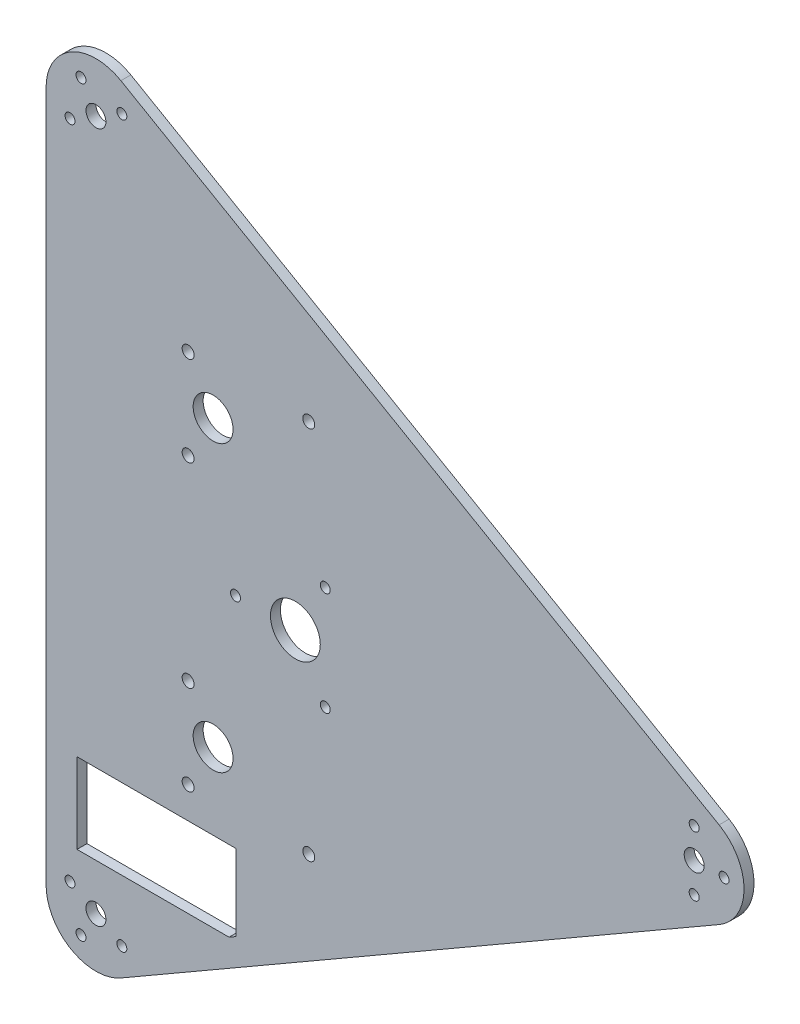
SolidWorks part; units mm, degrees
other "Frame3(PCB)"
material "Epoxy, Unfilled"
ref_plane "Front" through (0, 0, 0) normal (0, 0, 1) x (1, 0, 0)
ref_plane "Top" through (0, 0, 0) normal (0, 1, 0) x (1, 0, 0)
ref_plane "Right" through (0, 0, 0) normal (1, 0, 0) x (0, 0, -1)
sketch "BoardSke" plane through (0, 0, 0) normal (0, 0, 1) x (1, 0, 0)
  line L1 (42.5, 4.3301) -> (-17.5, 38.9711)
  line L2 (-25, 34.641) -> (-25, -34.641)
  line L3 (-17.5, -38.9711) -> (42.5, -4.3301)
  circle A0 centre (0, 0) radius 25 construction
  arc A1 (-25, -34.641) -> (-17.5, -38.9711) centre (-20, -34.641) ccw
  arc A2 (42.5, 4.3301) -> (42.5, -4.3301) centre (40, 0) cw
  arc A3 (-17.5, 38.9711) -> (-25, 34.641) centre (-20, 34.641) ccw
  dimension "D1" = 50
  dimension "D2" = 5
extrude "Board" add sketch "BoardSke" along normal blind 1 separate body
sketch "ESCSke" plane through (0, 0, 1) normal (0, 0, 1) x (1, 0, 0)
  line L0 (-21.9, 30) -> (-21.9, 21.951) construction
  line L1 (-21.9, 21.951) -> (-5.95, 21.951) construction
  line L2 (-5.95, 21.951) -> (-5.95, 29.6) construction
  line L3 (-5.95, 29.6) -> (-6.65, 30) construction
  line L4 (-6.65, 30) -> (-21.9, 30) construction
  line L5 (50, 0) -> (-50, 0) construction
  line L6 (-6.65, -30) -> (-21.9, -30)
  line L7 (-5.95, -29.6) -> (-6.65, -30)
  line L8 (-5.95, -21.951) -> (-5.95, -29.6)
  line L9 (-21.9, -21.951) -> (-5.95, -21.951)
  line L10 (-21.9, -30) -> (-21.9, -21.951)
  dimension "D1" = 8.049
  dimension "D2" = 15.95
  dimension "D3" = 7.649
  dimension "D4" = 15.25
  dimension "D5" = 30
  dimension "D6" = 21.9
extrude "ESC" cut sketch "ESCSke" against normal through all
sketch "Hole1Ske" plane through (0, 0, 1) normal (0, 0, 1) x (1, 0, 0)
  circle A0 centre (-6, 0) radius 0.5
  circle A1 centre (3, 5.1962) radius 0.5
  circle A2 centre (3, -5.1962) radius 0.5
  circle A3 centre (0, 0) radius 2.5
  point P9 (0, 0)
  dimension "D2" = 6
  dimension "D1" = 1
  dimension "D4" = 5
  dimension "D3" = 3
extrude "Hole1" cut sketch "Hole1Ske" against normal through all
sketch "Hole2Ske" plane through (0, 0, 1) normal (0, 0, 1) x (1, 0, 0)
  line L1 (0, 0) -> (40, 0) construction
  circle A2 centre (40, 0) radius 1
  circle A4 centre (-20, -34.641) radius 1
  circle A6 centre (-20, 34.641) radius 1
  point P18 (0, 0)
  dimension "D1" = 40
  dimension "D2" = 2
  dimension "D4" = 3
extrude "Hole2" cut sketch "Hole2Ske" against normal through all
sketch "Hole3Ske" plane through (0, 0, 1) normal (0, 0, 1) x (1, 0, 0)
  line L0 (40, 3) -> (40, -3) construction
  circle A0 centre (40, 0) radius 1 construction
  circle A1 centre (40, 0) radius 1 construction
  circle A2 centre (40, 3) radius 0.5
  circle A3 centre (40, -3) radius 0.5
  circle A4 centre (-22.5981, -33.141) radius 0.5
  circle A5 centre (-17.4019, -36.141) radius 0.5
  circle A6 centre (-17.4019, 36.141) radius 0.5
  circle A7 centre (-22.5981, 33.141) radius 0.5
  circle A8 centre (43, 0) radius 0.5
  circle A9 centre (-21.5, -37.2391) radius 0.5
  circle A10 centre (-21.5, 37.2391) radius 0.5
  point P19 (0, 0)
  dimension "D1" = 1
  dimension "D2" = 3
  dimension "D4" = 3
  dimension "D3" = 3
extrude "Hole3" cut sketch "Hole3Ske" against normal through all
sketch "MotorSetSke" plane through (0, 0, 1) normal (0, 0, 1) x (1, 0, 0)
  line L0 (-8.25, 14.2894) -> (-8.25, -14.2894) construction
  line L2 (0, 0) -> (-20, 34.641) construction
  circle A0 centre (-8.25, 14.2894) radius 2
  circle A1 centre (0, 0) radius 12.5 construction
  circle A2 centre (-8.25, 14.2894) radius 4 construction
  point P4 (-8.25, 0)
  dimension "D1" = 4
  dimension "D4" = 25
  dimension "D5" = 8
extrude "MotorSet" cut sketch "MotorSetSke" against normal through all
sketch "MotorSetHoleSke" plane through (0, 0, 1) normal (0, 0, 1) x (1, 0, 0)
  line L0 (-10.7545, 18.7894) -> (-10.7545, 9.7894) construction
  line L1 (-10.7545, 9.7894) -> (-8.25, 14.2894) construction
  line L2 (-8.25, 14.2894) -> (-10.7545, 18.7894) construction
  circle A0 centre (-10.7545, 18.7894) radius 0.6
  circle A1 centre (-10.7545, 9.7894) radius 0.6
  circle A2 centre (1.3455, 18.7894) radius 0.6
  dimension "D3" = 1.2
  dimension "D1" = 5.15
  dimension "D2" = 9
  dimension "D4" = 12.1
extrude "MotorSetHole" cut sketch "MotorSetHoleSke" against normal through all
mirror "Mirror" about plane through (0, 0, 0) normal (0, 1, 0) of "MotorSetHole", "MotorSet"
